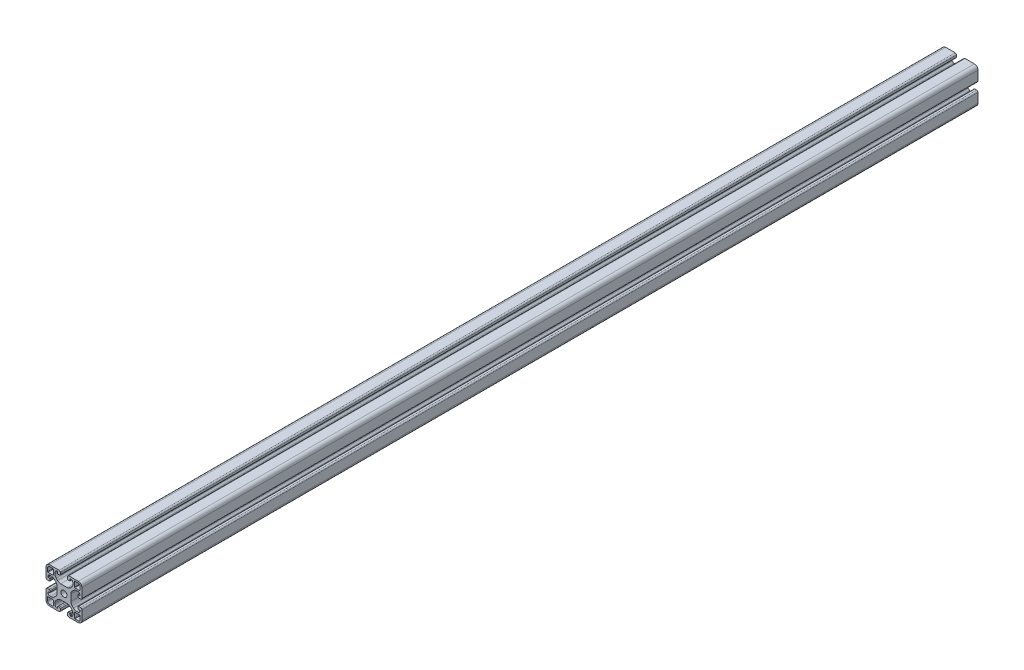
SolidWorks part; units mm, degrees
ref_plane "Front Plane" through (0, 0, 0) normal (0, 0, 1) x (1, 0, 0)
ref_plane "Top Plane" through (0, 0, 0) normal (0, 1, 0) x (1, 0, 0)
ref_plane "Right Plane" through (0, 0, 0) normal (1, 0, 0) x (0, 0, -1)
sketch "Sketch1" plane through (0, 0, 0) normal (0, 0, 1) x (1, 0, 0)
  line L0 (1.8, 4) -> (1.8, 7.7)
  line L1 (2.3, 8.2) -> (7.7, 8.2)
  line L2 (8.2, 7.7) -> (8.2, 2.3)
  line L3 (7.7, 1.8) -> (4, 1.8)
  line L4 (4, 38.2) -> (7.7, 38.2)
  line L5 (8.2, 37.7) -> (8.2, 32.3)
  line L6 (7.7, 31.8) -> (2.3, 31.8)
  line L7 (1.8, 32.3) -> (1.8, 36)
  line L8 (31.8, 32.3) -> (31.8, 37.7)
  line L9 (32.3, 38.2) -> (36, 38.2)
  line L10 (38.2, 36) -> (38.2, 32.3)
  line L11 (37.7, 31.8) -> (32.3, 31.8)
  line L12 (32.3, 8.2) -> (37.7, 8.2)
  line L13 (38.2, 7.7) -> (38.2, 4)
  line L14 (36, 1.8) -> (32.3, 1.8)
  line L15 (31.8, 2.3) -> (31.8, 7.7)
  line L16 (0, 36) -> (0, 25.5)
  line L17 (1.5, 24) -> (3.5, 24)
  line L18 (4.5, 25) -> (4.5, 26.5)
  line L19 (4, 27) -> (2.5, 27)
  line L20 (4.5, 30) -> (5.8076, 30)
  line L21 (9.3431, 28.5355) -> (10.7855, 27.0931)
  line L22 (12.25, 23.5576) -> (12.25, 16.4424)
  line L23 (10.7855, 12.9069) -> (9.3431, 11.4645)
  line L24 (5.8076, 10) -> (4.5, 10)
  line L25 (2.5, 13) -> (4, 13)
  line L26 (4.5, 13.5) -> (4.5, 15)
  line L27 (3.5, 16) -> (1.5, 16)
  line L28 (0, 14.5) -> (0, 4)
  line L29 (4, 0) -> (14.5, 0)
  line L30 (16, 1.5) -> (16, 3.5)
  line L31 (15, 4.5) -> (13.5, 4.5)
  line L32 (13, 4) -> (13, 2.5)
  line L33 (10, 4.5) -> (10, 5.8076)
  line L34 (11.4645, 9.3431) -> (12.9069, 10.7855)
  line L35 (16.4424, 12.25) -> (23.5576, 12.25)
  line L36 (27.0931, 10.7855) -> (28.5355, 9.3431)
  line L37 (30, 5.8076) -> (30, 4.5)
  line L38 (27, 2.5) -> (27, 4)
  line L39 (26.5, 4.5) -> (25, 4.5)
  line L40 (24, 3.5) -> (24, 1.5)
  line L41 (25.5, 0) -> (36, 0)
  line L42 (40, 4) -> (40, 14.5)
  line L43 (38.5, 16) -> (36.5, 16)
  line L44 (35.5, 15) -> (35.5, 13.5)
  line L45 (36, 13) -> (37.5, 13)
  line L46 (35.5, 10) -> (34.1924, 10)
  line L47 (30.6569, 11.4645) -> (29.2145, 12.9069)
  line L48 (27.75, 16.4424) -> (27.75, 23.5576)
  line L49 (29.2145, 27.0931) -> (30.6569, 28.5355)
  line L50 (34.1924, 30) -> (35.5, 30)
  line L51 (37.5, 27) -> (36, 27)
  line L52 (35.5, 26.5) -> (35.5, 25)
  line L53 (36.5, 24) -> (38.5, 24)
  line L54 (40, 25.5) -> (40, 36)
  line L55 (36, 40) -> (25.5, 40)
  line L56 (24, 38.5) -> (24, 36.5)
  line L57 (25, 35.5) -> (26.5, 35.5)
  line L58 (27, 36) -> (27, 37.5)
  line L59 (30, 35.5) -> (30, 34.1924)
  line L60 (28.5355, 30.6569) -> (27.0931, 29.2145)
  line L61 (23.5576, 27.75) -> (16.4424, 27.75)
  line L62 (12.9069, 29.2145) -> (11.4645, 30.6569)
  line L63 (10, 34.1924) -> (10, 35.5)
  line L64 (13, 37.5) -> (13, 36)
  line L65 (13.5, 35.5) -> (15, 35.5)
  line L66 (16, 36.5) -> (16, 38.5)
  line L67 (14.5, 40) -> (4, 40)
  arc A0 (1.8, 7.7) -> (2.3, 8.2) centre (2.3, 7.7) cw
  arc A1 (7.7, 8.2) -> (8.2, 7.7) centre (7.7, 7.7) cw
  arc A2 (8.2, 2.3) -> (7.7, 1.8) centre (7.7, 2.3) cw
  arc A3 (4, 1.8) -> (1.8, 4) centre (4, 4) cw
  arc A4 (1.8, 36) -> (4, 38.2) centre (4, 36) cw
  arc A5 (7.7, 38.2) -> (8.2, 37.7) centre (7.7, 37.7) cw
  arc A6 (8.2, 32.3) -> (7.7, 31.8) centre (7.7, 32.3) cw
  arc A7 (2.3, 31.8) -> (1.8, 32.3) centre (2.3, 32.3) cw
  circle A8 centre (20, 20) radius 3.4
  arc A9 (31.8, 37.7) -> (32.3, 38.2) centre (32.3, 37.7) cw
  arc A10 (36, 38.2) -> (38.2, 36) centre (36, 36) cw
  arc A11 (38.2, 32.3) -> (37.7, 31.8) centre (37.7, 32.3) cw
  arc A12 (32.3, 31.8) -> (31.8, 32.3) centre (32.3, 32.3) cw
  arc A13 (31.8, 7.7) -> (32.3, 8.2) centre (32.3, 7.7) cw
  arc A14 (37.7, 8.2) -> (38.2, 7.7) centre (37.7, 7.7) cw
  arc A15 (38.2, 4) -> (36, 1.8) centre (36, 4) cw
  arc A16 (32.3, 1.8) -> (31.8, 2.3) centre (32.3, 2.3) cw
  arc A17 (0, 25.5) -> (1.5, 24) centre (1.5, 25.5) ccw
  arc A18 (3.5, 24) -> (4.5, 25) centre (3.5, 25) ccw
  arc A19 (4.5, 26.5) -> (4, 27) centre (4, 26.5) ccw
  arc A20 (2.5, 27) -> (2, 27.5) centre (2.5, 27.5) cw
  arc A21 (2, 27.5) -> (4.5, 30) centre (4.5, 27.5) cw
  arc A22 (5.8076, 30) -> (9.3431, 28.5355) centre (5.8076, 25) cw
  arc A23 (10.7855, 27.0931) -> (12.25, 23.5576) centre (7.25, 23.5576) cw
  arc A24 (12.25, 16.4424) -> (10.7855, 12.9069) centre (7.25, 16.4424) cw
  arc A25 (9.3431, 11.4645) -> (5.8076, 10) centre (5.8076, 15) cw
  arc A26 (4.5, 10) -> (2, 12.5) centre (4.5, 12.5) cw
  arc A27 (2, 12.5) -> (2.5, 13) centre (2.5, 12.5) cw
  arc A28 (4, 13) -> (4.5, 13.5) centre (4, 13.5) ccw
  arc A29 (4.5, 15) -> (3.5, 16) centre (3.5, 15) ccw
  arc A30 (1.5, 16) -> (0, 14.5) centre (1.5, 14.5) ccw
  arc A31 (0, 4) -> (4, 0) centre (4, 4) ccw
  arc A32 (14.5, 0) -> (16, 1.5) centre (14.5, 1.5) ccw
  arc A33 (16, 3.5) -> (15, 4.5) centre (15, 3.5) ccw
  arc A34 (13.5, 4.5) -> (13, 4) centre (13.5, 4) ccw
  arc A35 (13, 2.5) -> (12.5, 2) centre (12.5, 2.5) cw
  arc A36 (12.5, 2) -> (10, 4.5) centre (12.5, 4.5) cw
  arc A37 (10, 5.8076) -> (11.4645, 9.3431) centre (15, 5.8076) cw
  arc A38 (12.9069, 10.7855) -> (16.4424, 12.25) centre (16.4424, 7.25) cw
  arc A39 (23.5576, 12.25) -> (27.0931, 10.7855) centre (23.5576, 7.25) cw
  arc A40 (28.5355, 9.3431) -> (30, 5.8076) centre (25, 5.8076) cw
  arc A41 (30, 4.5) -> (27.5, 2) centre (27.5, 4.5) cw
  arc A42 (27.5, 2) -> (27, 2.5) centre (27.5, 2.5) cw
  arc A43 (27, 4) -> (26.5, 4.5) centre (26.5, 4) ccw
  arc A44 (25, 4.5) -> (24, 3.5) centre (25, 3.5) ccw
  arc A45 (24, 1.5) -> (25.5, 0) centre (25.5, 1.5) ccw
  arc A46 (36, 0) -> (40, 4) centre (36, 4) ccw
  arc A47 (40, 14.5) -> (38.5, 16) centre (38.5, 14.5) ccw
  arc A48 (36.5, 16) -> (35.5, 15) centre (36.5, 15) ccw
  arc A49 (35.5, 13.5) -> (36, 13) centre (36, 13.5) ccw
  arc A50 (37.5, 13) -> (38, 12.5) centre (37.5, 12.5) cw
  arc A51 (38, 12.5) -> (35.5, 10) centre (35.5, 12.5) cw
  arc A52 (34.1924, 10) -> (30.6569, 11.4645) centre (34.1924, 15) cw
  arc A53 (29.2145, 12.9069) -> (27.75, 16.4424) centre (32.75, 16.4424) cw
  arc A54 (27.75, 23.5576) -> (29.2145, 27.0931) centre (32.75, 23.5576) cw
  arc A55 (30.6569, 28.5355) -> (34.1924, 30) centre (34.1924, 25) cw
  arc A56 (35.5, 30) -> (38, 27.5) centre (35.5, 27.5) cw
  arc A57 (38, 27.5) -> (37.5, 27) centre (37.5, 27.5) cw
  arc A58 (36, 27) -> (35.5, 26.5) centre (36, 26.5) ccw
  arc A59 (35.5, 25) -> (36.5, 24) centre (36.5, 25) ccw
  arc A60 (38.5, 24) -> (40, 25.5) centre (38.5, 25.5) ccw
  arc A61 (40, 36) -> (36, 40) centre (36, 36) ccw
  arc A62 (25.5, 40) -> (24, 38.5) centre (25.5, 38.5) ccw
  arc A63 (24, 36.5) -> (25, 35.5) centre (25, 36.5) ccw
  arc A64 (26.5, 35.5) -> (27, 36) centre (26.5, 36) ccw
  arc A65 (27, 37.5) -> (27.5, 38) centre (27.5, 37.5) cw
  arc A66 (27.5, 38) -> (30, 35.5) centre (27.5, 35.5) cw
  arc A67 (30, 34.1924) -> (28.5355, 30.6569) centre (25, 34.1924) cw
  arc A68 (27.0931, 29.2145) -> (23.5576, 27.75) centre (23.5576, 32.75) cw
  arc A69 (16.4424, 27.75) -> (12.9069, 29.2145) centre (16.4424, 32.75) cw
  arc A70 (11.4645, 30.6569) -> (10, 34.1924) centre (15, 34.1924) cw
  arc A71 (10, 35.5) -> (12.5, 38) centre (12.5, 35.5) cw
  arc A72 (12.5, 38) -> (13, 37.5) centre (12.5, 37.5) cw
  arc A73 (13, 36) -> (13.5, 35.5) centre (13.5, 36) ccw
  arc A74 (15, 35.5) -> (16, 36.5) centre (15, 36.5) ccw
  arc A75 (16, 38.5) -> (14.5, 40) centre (14.5, 38.5) ccw
  arc A76 (4, 40) -> (0, 36) centre (4, 36) ccw
  point P219 (0, 0)
  dimension "D1" = 20
  dimension "D2" = 20
  dimension "D3" = 6.8
  dimension "D4" = 15.5
  dimension "D5" = 15.5
extrude "Boss-Extrude1" add sketch "Sketch1" against normal blind 1000
